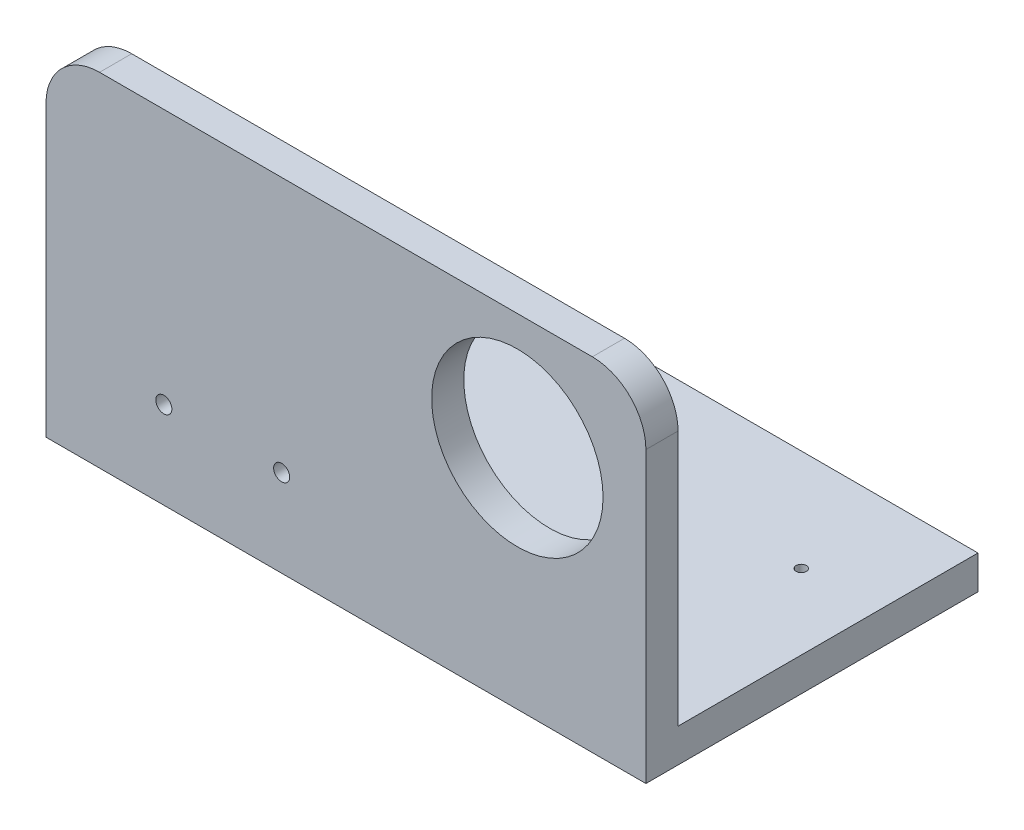
SolidWorks part; units mm, degrees
ref_plane "Front Plane" through (0, 0, 0) normal (0, 0, 1) x (1, 0, 0)
ref_plane "Top Plane" through (0, 0, 0) normal (0, 1, 0) x (1, 0, 0)
ref_plane "Right Plane" through (0, 0, 0) normal (1, 0, 0) x (0, 0, -1)
sketch "Sketch1" plane through (0, 0, 0) normal (0, 1, 0) x (1, 0, 0)
  line L0 (95.25, 117.475) -> (95.25, 31.75) construction
  line L1 (0, 0) -> (355.6, 0)
  line L2 (0, 0) -> (0, 177.8)
  line L3 (0, 177.8) -> (355.6, 177.8)
  line L4 (355.6, 0) -> (355.6, 177.8)
  line L5 (95.25, 31.75) -> (311.15, 31.75) construction
  line L6 (311.15, 31.75) -> (311.15, 117.475) construction
  line L7 (311.15, 117.475) -> (95.25, 117.475) construction
  circle A0 centre (95.25, 117.475) radius 3.048
  circle A1 centre (311.15, 117.475) radius 3.048
  circle A2 centre (311.15, 31.75) radius 3.048
  circle A3 centre (95.25, 31.75) radius 3.048
  dimension "D3" = 6.096
  dimension "D6" = 95.25
  dimension "D7" = 31.75
  dimension "D1" = 355.6
  dimension "D2" = 177.8
  dimension "D4" = 85.725
  dimension "D5" = 215.9
extrude "Boss-Extrude1" add sketch "Sketch1" along normal blind 19.939
sketch "Sketch2" plane through (0, 0, 0) normal (0, 1, 0) x (1, 0, 0)
  line L1 (0, 0) -> (355.6, 0)
  line L2 (0, 0) -> (0, -19.05)
  line L3 (0, -19.05) -> (355.6, -19.05)
  line L4 (355.6, 0) -> (355.6, -19.05)
  dimension "D1" = 19.05
extrude "Boss-Extrude2" add sketch "Sketch2" along normal blind 203.2
sketch "Sketch3" plane through (0, 0, 19.05) normal (0, 0, 1) x (1, 0, 0)
  line L0 (279.4, 134.239) -> (279.4, 0) construction
  line L1 (0, 0) -> (355.6, 0) construction
  line L2 (69.85, 51.689) -> (139.7, 51.689) construction
  line L3 (0, 203.2) -> (0, 0) construction
  line L5 (0, 19.939) -> (355.6, 19.939) construction
  circle A0 centre (279.4, 134.239) radius 50.8
  circle A1 centre (69.85, 51.689) radius 4.7625
  circle A2 centre (139.7, 51.689) radius 4.7625
  dimension "D1" = 101.6
  dimension "D2" = 9.525
  dimension "D3" = 69.85
  dimension "D4" = 69.85
  dimension "D5" = 31.75
  dimension "D6" = 114.3
  dimension "D7" = 139.7
extrude "Cut-Extrude1" cut sketch "Sketch3" against normal through all
fillet "Fillet1" radius 31.75 2 edges at (355.6, 203.2, 9.525) (0, 203.2, 9.525)
